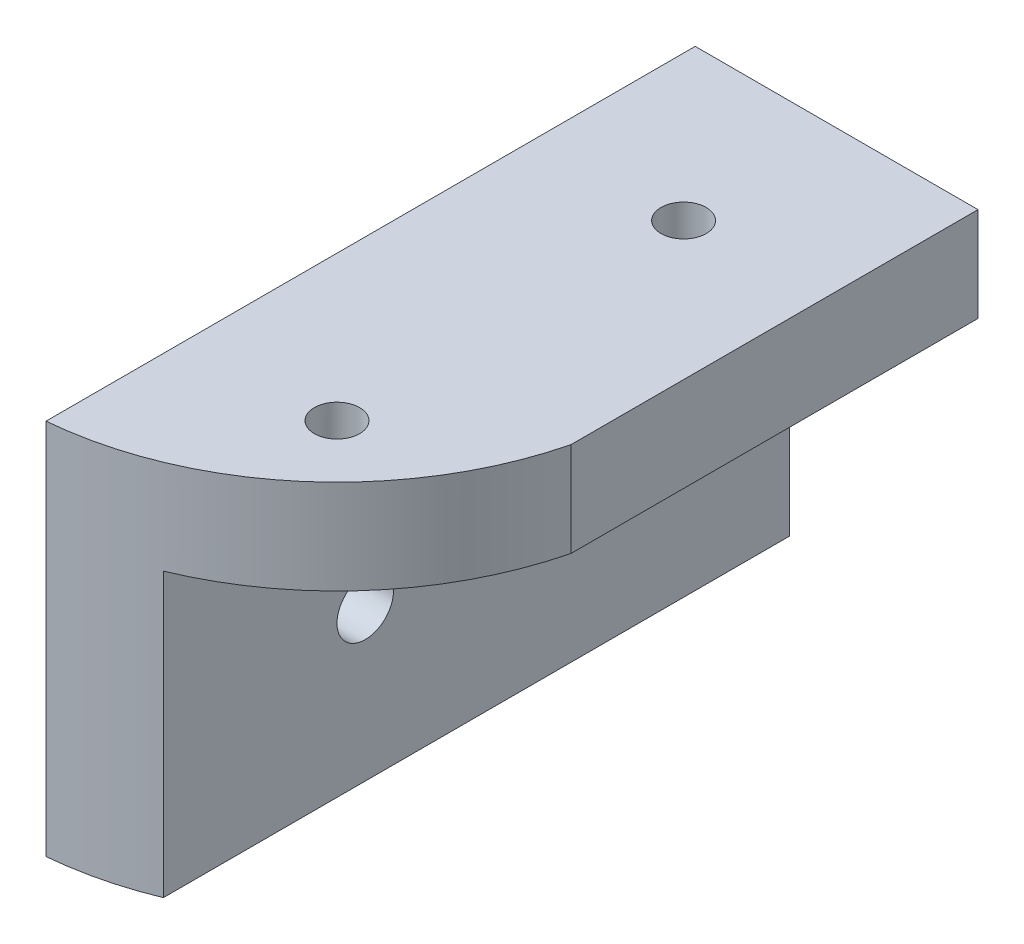
SolidWorks part; units mm, degrees
ref_plane "Front Plane" through (0, 0, 0) normal (0, 0, 1) x (1, 0, 0)
ref_plane "Top Plane" through (0, 0, 0) normal (0, 1, 0) x (1, 0, 0)
ref_plane "Right Plane" through (0, 0, 0) normal (1, 0, 0) x (0, 0, -1)
sketch "Sketch1" plane through (0, 0, 0) normal (0, 0, 1) x (1, 0, 0)
  line L0 (0, 0) -> (0, 20)
  line L1 (0, 20) -> (15, 20)
  line L2 (15, 20) -> (15, 15)
  line L3 (15, 15) -> (5, 15)
  line L4 (5, 15) -> (5, 0)
  line L5 (5, 0) -> (0, 0)
  dimension "D1" = 20
  dimension "D2" = 15
  dimension "D3" = 5
  dimension "D4" = 5
extrude "Boss-Extrude1" add sketch "Sketch1" along normal blind 35
sketch "Sketch3" plane through (0, 15, 0) normal (0, -1, 0) x (1, 0, 0)
  line L0 (7.6924, 26.6924) -> (7.6924, 8.3076) construction
  line L3 (5, 0) -> (15, 0) construction
  line L4 (5, 35) -> (15, 35) construction
  line L5 (7.6924, 8.3076) -> (-1.5, 17.5) construction
  line L6 (-1.5, 17.5) -> (7.6924, 26.6924) construction
  line L7 (0, 35) -> (0, 0) construction
  circle A0 centre (7.6924, 26.6924) radius 1.2
  circle A1 centre (7.6924, 8.3076) radius 1.2
  point P6 (7.6924, 17.5)
  point P9 (10, 0)
  dimension "D1" = 2.4
  dimension "D2" = 2.4
  dimension "D5" = 17.5
  dimension "D6" = 17.5
  dimension "D3" = 13
  dimension "D7" = 13
  dimension "D8" = 18.3848
  dimension "D4" = 1.5
extrude "Cut-Extrude1" cut sketch "Sketch3" against normal up to next
sketch "Sketch4" plane through (5, 0, 0) normal (1, 0, 0) x (0, 0, -1)
  line L0 (-22.5, 8) -> (-12.5, 8) construction
  line L1 (-35, 0) -> (-35, 15) construction
  line L2 (0, 0) -> (0, 15) construction
  line L4 (-35, 20) -> (0, 20) construction
  circle A0 centre (-22.5, 8) radius 1.5
  circle A1 centre (-12.5, 8) radius 1.5
  point P6 (-17.5, 8)
  dimension "D1" = 10
  dimension "D2" = 3
  dimension "D3" = 17.5
  dimension "D4" = 17.5
  dimension "D5" = 12
extrude "Cut-Extrude2" cut sketch "Sketch4" against normal up to next
sketch "Sketch6" plane through (0, 20, 0) normal (0, 1, 0) x (1, 0, 0)
  line L2 (-1.5, -34.5) -> (-1.5, -42.5)
  line L3 (15.5, -17.5) -> (23.5, -17.5)
  line L4 (15.5, -17.5) -> (-1.5, -17.5) construction
  line L5 (-1.5, -17.5) -> (-1.5, -34.5) construction
  circle A0 centre (-1.5, -17.5) radius 17 construction
  arc A1 (15.5, -17.5) -> (-1.5, -34.5) centre (-1.5, -17.5) cw
  arc A2 (-1.5, -42.5) -> (23.5, -17.5) centre (-1.5, -17.5) ccw
  dimension "D1" = 34
  dimension "D3" = 8
extrude "Cut-Extrude4" cut sketch "Sketch6" against normal up to next
sketch "Sketch5" plane through (0, 20, 0) normal (0, 1, 0) x (1, 0, 0)
  line L0 (15, -21.5927) -> (15, 0) construction
  line L1 (0, 0) -> (15, 0)
  line L2 (0, 0) -> (0, -35)
  line L3 (0, -35) -> (15, -35)
  line L4 (15, 0) -> (15, -35)
  dimension "D1" = 35
equation "\"D1@Sketch3\"=\"D2@Sketch3\""
